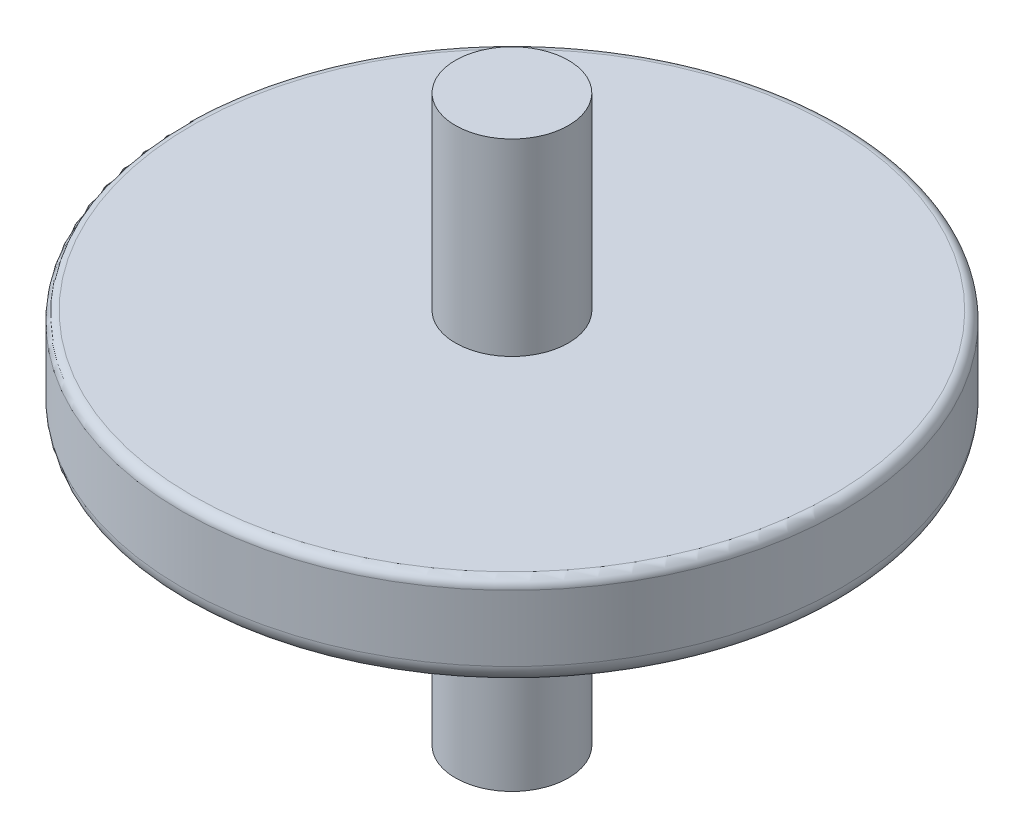
SolidWorks part; units mm, degrees
ref_plane "Front Plane" through (0, 0, 0) normal (0, 0, 1) x (1, 0, 0)
ref_plane "Top Plane" through (0, 0, 0) normal (0, 1, 0) x (1, 0, 0)
ref_plane "Right Plane" through (0, 0, 0) normal (1, 0, 0) x (0, 0, -1)
sketch "Sketch1" plane through (0, 0, 0) normal (0, 1, 0) x (1, 0, 0)
  circle A0 centre (0, 0) radius 3
extrude "Boss-Extrude1" add sketch "Sketch1" along normal blind 15
sketch "Sketch3" plane through (0, 15, 0) normal (0, 1, 0) x (1, 0, 0)
  circle A0 centre (0, 0) radius 17.5
extrude "Boss-Extrude2" add sketch "Sketch3" along normal blind 5
sketch "Sketch4" plane through (0, 20, 0) normal (0, 1, 0) x (1, 0, 0)
  circle A0 centre (0, 0) radius 3
extrude "Boss-Extrude3" add sketch "Sketch4" along normal blind 10
fillet "Fillet4" radius 1 1 edges at (0, 15, 17.5)
fillet "Fillet5" radius 0.5 1 edges at (0, 20, 17.5)
